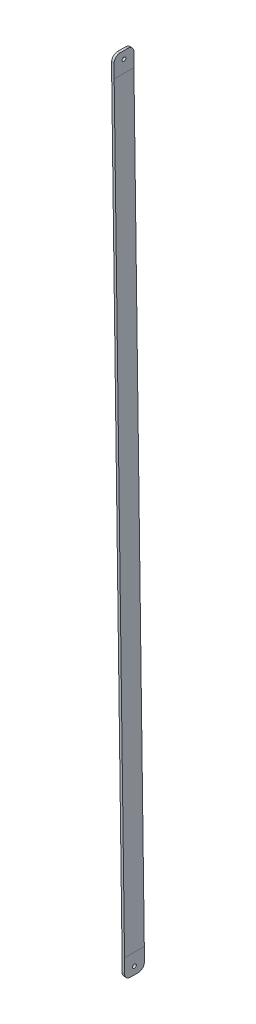
SolidWorks part; units mm, degrees
material "6061 Alloy"
ref_plane "Front Plane" through (0, 0, 0) normal (0, 0, 1) x (1, 0, 0)
ref_plane "Top Plane" through (0, 0, 0) normal (0, 1, 0) x (1, 0, 0)
ref_plane "Right Plane" through (0, 0, 0) normal (1, 0, 0) x (0, 0, -1)
sketch "Sketch1" plane through (0, 0, 0) normal (0, 0, 1) x (1, 0, 0)
  line L0 (0, 0) -> (3.175, 0)
  line L1 (3.175, 0) -> (3.175, 25.4)
  line L2 (0, 0) -> (0, 25.4)
  line L3 (3.175, 25.4) -> (-10.16, 996.95)
  line L4 (0, 25.4) -> (-13.335, 996.95)
  line L5 (-10.16, 996.95) -> (-10.16, 1022.35)
  line L6 (-13.335, 1022.35) -> (-13.335, 996.95)
  line L7 (-13.335, 1022.35) -> (-10.16, 1022.35)
  point P9 (1.5875, 0)
  dimension "D1" = 25.4
  dimension "D2" = 3.175
  dimension "D3" = 25.4
  dimension "D4" = 13.335
  dimension "D5" = 25.4
  dimension "D6" = 25.4
  dimension "D7" = 1022.35
extrude "Boss-Extrude1" add sketch "Sketch1" along normal mid plane 25.4
fillet "Fillet1" radius 7.62 4 edges at (1.5875, 0, 12.7) (1.5875, 0, -12.7) (-11.7475, 1022.35, -12.7) (-11.7475, 1022.35, 12.7)
sketch "Sketch2" plane through (-10.16, 0, 0) normal (1, 0, 0) x (0, 0, -1)
  line L0 (-5.08, 1022.35) -> (5.08, 1022.35) construction
  circle A0 centre (0, 1012.698) radius 2.413
  circle A1 centre (0, 9.652) radius 2.413
  dimension "D1" = 4.826
  dimension "D2" = 4.826
  dimension "D3" = 9.652
  dimension "D4" = 1003.046
extrude "Cut-Extrude1" cut sketch "Sketch2" against normal through all and the other way through all
